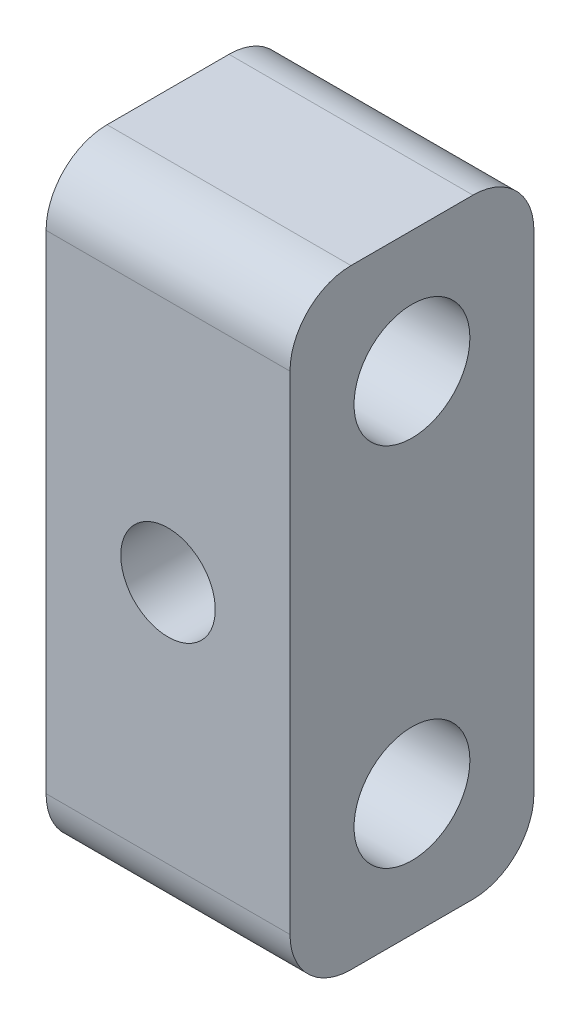
SolidWorks part; units mm, degrees
material "ABS"
ref_plane "Front" through (0, 0, 0) normal (0, 0, 1) x (1, 0, 0)
ref_plane "Top" through (0, 0, 0) normal (0, 1, 0) x (1, 0, 0)
ref_plane "Right" through (0, 0, 0) normal (1, 0, 0) x (0, 0, -1)
sketch "Esquisse1" plane through (0, 0, 0) normal (1, 0, 0) x (0, 0, -1)
  line L1 (-4, -10) -> (4, -10)
  line L2 (-4, -10) -> (-4, 10)
  line L3 (-4, 10) -> (4, 10)
  line L4 (4, -10) -> (4, 10)
  line L5 (0, 10) -> (0, -10) construction
  line L6 (-4, 0) -> (4, 0) construction
  circle A0 centre (0, 6) radius 1.55
  circle A1 centre (0, -6) radius 1.55
  point P0 (0, 0)
  dimension "D3" = 3.1
  dimension "D4" = 12
  dimension "D1" = 20
  dimension "D2" = 8
extrude "Boss.-Extru.1" add sketch "Esquisse1" along normal blind 8
sketch "Esquisse2" plane through (0, 0, -4) normal (0, 0, -1) x (-1, 0, 0)
  line L0 (-8, 10) -> (0, 10) construction
  circle A0 centre (-4, 0) radius 1.55
  point P5 (-4, 10)
  dimension "D1" = 3.1
extrude "Enlèv. mat.-Extru.1" cut sketch "Esquisse2" against normal through all
sketch "Esquisse3" plane through (8, 0, 0) normal (1, 0, 0) x (0, 0, -1)
  circle A0 centre (0, 6) radius 1.9
  circle A1 centre (0, -6) radius 1.9
  circle A2 centre (0, -6) radius 1.55 construction
  circle A3 centre (0, 6) radius 1.55 construction
  dimension "D1" = 3.8
extrude "Enlèv. mat.-Extru.2" cut sketch "Esquisse3" against normal blind 3
sketch "Esquisse4" plane through (0, 0, -4) normal (0, 0, -1) x (-1, 0, 0)
  line L1 (-5.5877, 2.75) -> (-7.1754, 0)
  line L2 (-7.1754, 0) -> (-5.5877, -2.75)
  line L3 (-5.5877, -2.75) -> (-2.4123, -2.75)
  line L4 (-2.4123, -2.75) -> (-0.8246, 0)
  line L5 (-0.8246, 0) -> (-2.4123, 2.75)
  line L6 (-2.4123, 2.75) -> (-5.5877, 2.75)
  circle A0 centre (-4, 0) radius 2.75 construction
  circle A1 centre (-4, 0) radius 1.55 construction
  dimension "D1" = 5.5
extrude "Enlèv. mat.-Extru.3" cut sketch "Esquisse4" against normal blind 5
fillet "Congé1" radius 2 4 edges at (4, -10, 4) (4, 10, 4) (4, 10, -4) (4, -10, -4)
